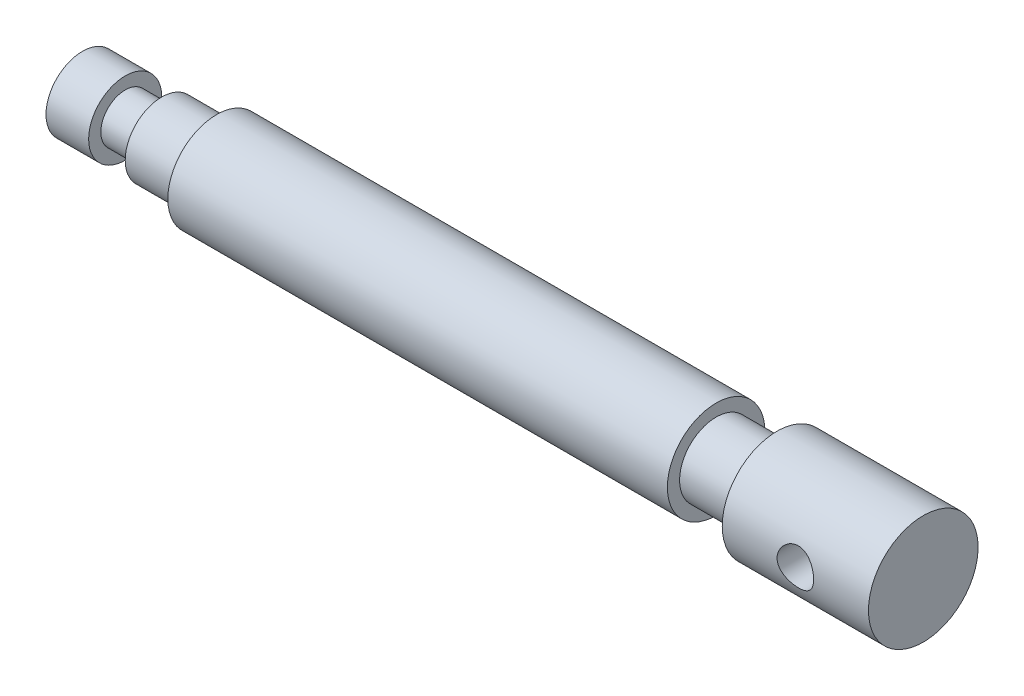
SolidWorks part; units mm, degrees
ref_plane "Front Plane" through (0, 0, 0) normal (0, 0, 1) x (1, 0, 0)
ref_plane "Top Plane" through (0, 0, 0) normal (0, 1, 0) x (1, 0, 0)
ref_plane "Right Plane" through (0, 0, 0) normal (1, 0, 0) x (0, 0, -1)
sketch "Sketch2" plane through (0, 0, 0) normal (0, 0, 1) x (1, 0, 0)
  line L0 (0, 0) -> (0, 6)
  line L1 (0, 6) -> (7, 6)
  line L2 (7, 6) -> (7, 4)
  line L3 (7, 4) -> (13, 4)
  line L4 (13, 4) -> (13, 6)
  line L5 (13, 6) -> (22, 6)
  line L6 (22, 6) -> (22, 8)
  line L7 (22, 8) -> (104, 8)
  line L8 (104, 8) -> (104, 6)
  line L9 (104, 6) -> (114, 6)
  line L10 (114, 6) -> (114, 9)
  line L11 (114, 9) -> (138, 9)
  line L12 (138, 9) -> (138, 0)
  line L13 (-23.4007, 0) -> (167.3005, 0) construction
  line L14 (0, 0) -> (138, 0)
revolve "Revolve1" add sketch "Sketch2" angle 360 about L13
hole_wizard "Ø6.0 (6) Diameter Hole3" positions "3DSketch7" profile "Sketch9" hole size "Ø6.0" standard "Ansi Metric" end condition through all
sketch3d "3DSketch7"
  point P0 (126, -0.056, 8.9998)
sketch "Sketch9" plane through (126, -0.056, 8.9998) normal (1, 0, 0) x (0, -1, -0.0062)
  line L0 (0, 0) -> (0, 18.0558)
  line L1 (0, 18.0558) -> (3, 18.0558)
  line L2 (3, 18.0558) -> (3, 0)
  line L5 (3, 0) -> (0, 0)
  line L11 (0, -6.35) -> (0, 107.95) construction
  dimension "Thru Hole Dia." = 6
  dimension "Thru Hole Depth" = 18.0558
